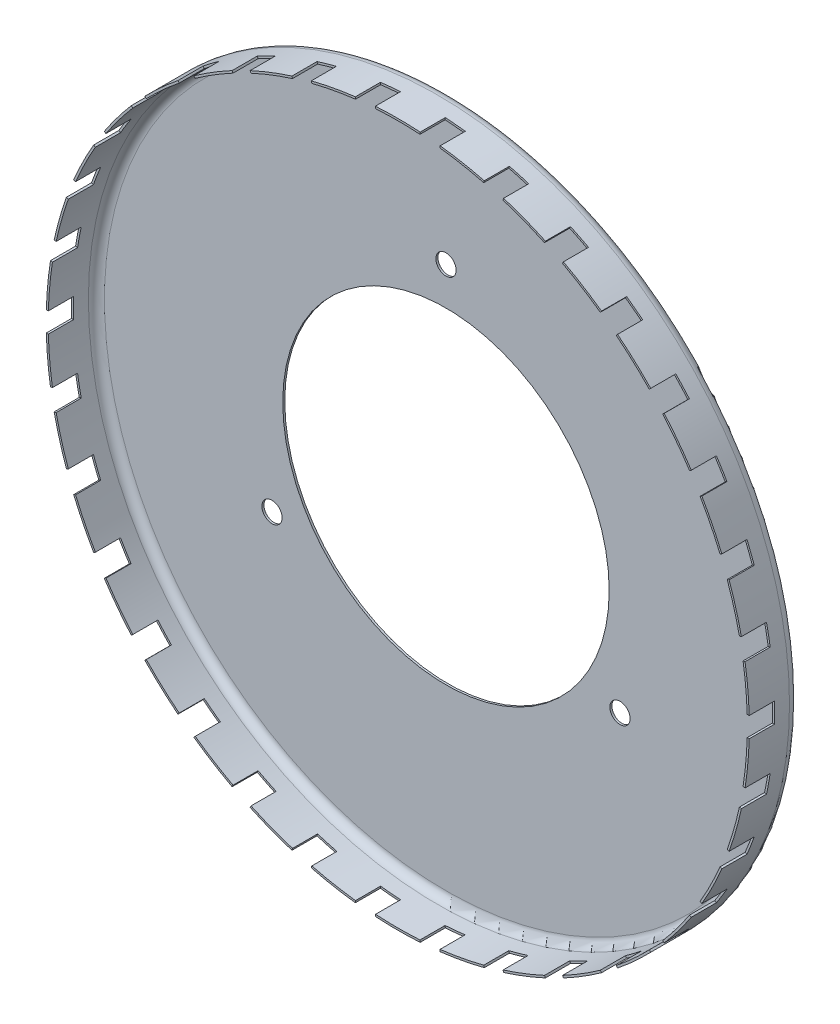
SolidWorks part; units mm, degrees
material "Chrome Stainless Steel"
ref_plane "Front" through (0, 0, 0) normal (0, 0, 1) x (1, 0, 0)
ref_plane "Top" through (0, 0, 0) normal (0, 1, 0) x (1, 0, 0)
ref_plane "Right" through (0, 0, 0) normal (1, 0, 0) x (0, 0, -1)
sketch "Sketch1" plane through (0, 0, 0) normal (0, 0, 1) x (1, 0, 0)
  circle A0 centre (0, 0) radius 88.9
extrude "Extrude1" add sketch "Sketch1" along normal blind 12.7
fillet "Fillet1" radius 2.54 1 edges at (88.9, 0, 0)
shell "Shell1" thickness 0.508
hole_wizard "1 (1) Diameter Hole1" positions "3DSketch1" profile "Sketch2" hole size "1" standard "Ansi Inch"
sketch3d "3DSketch1"
  point P0 (0, 0, 0.508)
sketch "Sketch2" plane through (0, 0, 0.508) normal (1, 0, 0) x (0, -1, 0)
  line L0 (0, 0) -> (0, 42.5805)
  line L1 (0, 42.5805) -> (41.275, 17.78)
  line L2 (41.275, 17.78) -> (41.275, 0)
  line L5 (41.275, 0) -> (0, 0)
  line L10 (0, 42.5805) -> (-41.275, 17.78) construction
  line L11 (0, -6.35) -> (0, 107.95) construction
  dimension "Hole Dia." = 82.55
  dimension "Hole Depth" = 17.78
  dimension "Drill Angle" = 118
sketch "Sketch3" plane through (0, 0, 0) normal (1, 0, 0) x (0, 0, -1)
  line L0 (-12.7, 0) -> (-6.35, 0) construction
  line L1 (-12.7, 88.9) -> (-12.7, -88.9) construction
  line L2 (-12.7, -2.54) -> (-12.7, 2.54)
  line L3 (-12.7, 2.54) -> (-6.35, 2.54)
  line L4 (-6.35, 2.54) -> (-6.35, -2.54)
  line L5 (-12.7, -2.54) -> (-6.35, -2.54)
extrude "Extrude2" cut sketch "Sketch3" against normal through all and the other way through all
pattern_circular "CirPattern1" count 17 over 360 about axis through (0, 0, 0) along (0, 0, 1) of "Extrude2"
hole_wizard "#10 Clearance Hole1" positions "3DSketch2" profile "Sketch4" hole size "#10" standard "Ansi Inch" end condition through all
sketch3d "3DSketch2"
  point P0 (0, 50.8, 0.508)
sketch "Sketch4" plane through (0, 50.8, 0.508) normal (1, 0, 0) x (0, -1, 0)
  line L0 (0, 0) -> (0, 0.508)
  line L1 (0, 0.508) -> (2.5527, 0.508)
  line L2 (2.5527, 0.508) -> (2.5527, 0)
  line L5 (2.5527, 0) -> (0, 0)
  line L11 (0, -6.35) -> (0, 107.95) construction
  dimension "Thru Hole Dia." = 5.1054
  dimension "Thru Hole Depth" = 0.508
pattern_circular "CirPattern2" count 3 over 360 about axis through (0, 0, 0) along (0, 0, 1) of "#10 Clearance Hole1"
